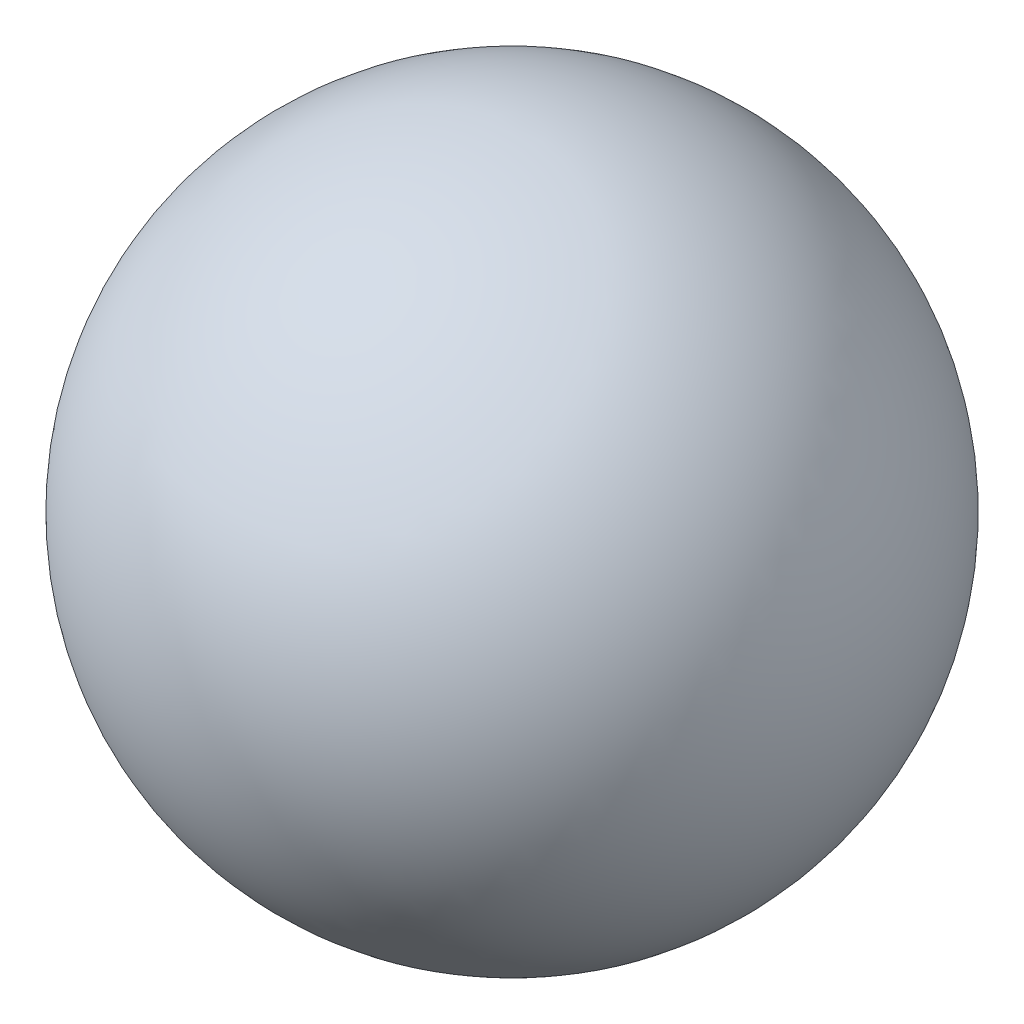
SolidWorks part; units mm, degrees
ref_plane "前视基准面" through (0, 0, 0) normal (0, 0, 1) x (1, 0, 0)
ref_plane "上视基准面" through (0, 0, 0) normal (0, 1, 0) x (1, 0, 0)
ref_plane "右视基准面" through (0, 0, 0) normal (1, 0, 0) x (0, 0, -1)
sketch "草图1" plane through (0, 0, 0) normal (0, 0, 1) x (1, 0, 0)
  line L0 (0, 25.1428) -> (0, -30.8369) construction
  circle A0 centre (0, 0) radius 21
revolve "旋转3" add sketch "草图1" angle 360 about L0
